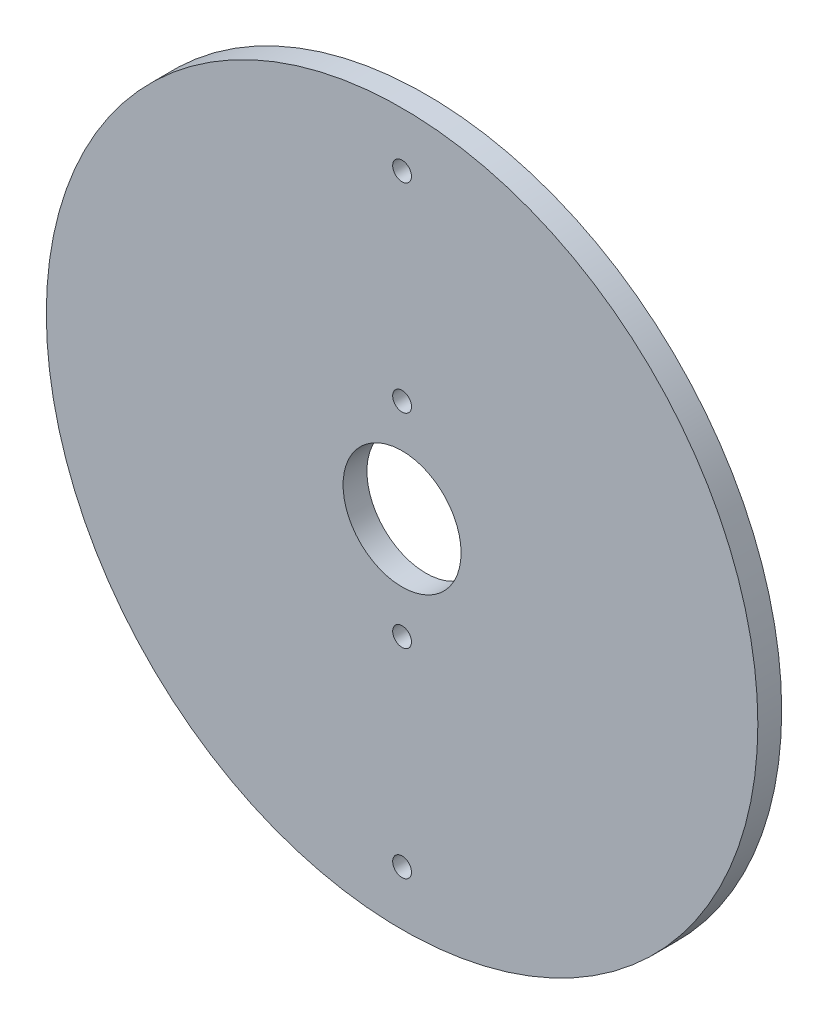
SolidWorks part; units mm, degrees
material "Cedar"
ref_plane "Front Plane" through (0, 0, 0) normal (0, 0, 1) x (1, 0, 0)
ref_plane "Top Plane" through (0, 0, 0) normal (0, 1, 0) x (1, 0, 0)
ref_plane "Right Plane" through (0, 0, 0) normal (1, 0, 0) x (0, 0, -1)
sketch "Sketch1" plane through (0, 0, 0) normal (0, 0, 1) x (1, 0, 0)
  line L0 (0, 56.159) -> (0, -56.159) construction
  circle A0 centre (0, 0) radius 66.319
  circle A1 centre (0, 18.9992) radius 1.7526
  circle A2 centre (0, 0) radius 10.9982
  circle A3 centre (0, -18.9992) radius 1.7526
  circle A4 centre (0, 56.159) radius 1.7526
  circle A5 centre (0, -56.159) radius 1.7526
  point P12 (0, 0)
  point P13 (0, 66.319)
  dimension "D1" = 10.16
  dimension "D2" = 3.5052
  dimension "D4" = 21.9964
  dimension "D5" = 3.5052
  dimension "D7" = 112.318
  dimension "D3" = 18.9992
  dimension "D6" = 18.9992
extrude "Boss-Extrude1" add sketch "Sketch1" along normal blind 4.445
